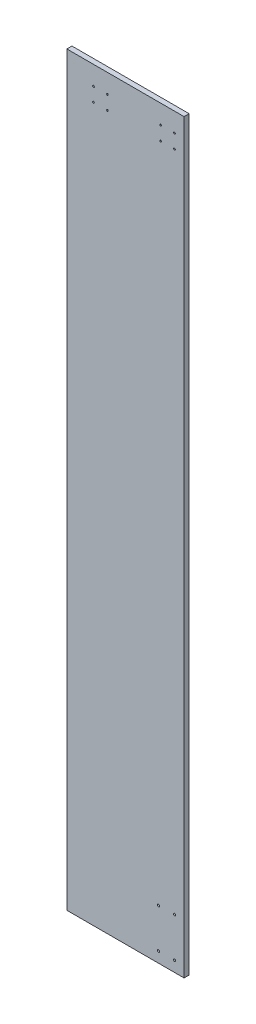
SolidWorks part; units mm, degrees
ref_plane "Front Plane" through (0, 0, 0) normal (0, 0, 1) x (1, 0, 0)
ref_plane "Top Plane" through (0, 0, 0) normal (0, 1, 0) x (1, 0, 0)
ref_plane "Right Plane" through (0, 0, 0) normal (1, 0, 0) x (0, 0, -1)
sketch "Sketch1" plane through (0, 0, 0) normal (0, 0, 1) x (-1, 0, 0)
  line L1 (0, 0) -> (-220, 0)
  line L2 (0, 0) -> (0, -1400)
  line L3 (0, -1400) -> (-220, -1400)
  line L4 (-220, 0) -> (-220, -1400)
  circle A12 centre (-202, -20) radius 2.065
  circle A13 centre (-172, -20) radius 2.065
  circle A14 centre (-202, -94) radius 2.065
  circle A15 centre (-172, -94) radius 2.065
  circle A16 centre (-202, -1338.2) radius 1.621
  circle A17 centre (-176, -1338.2) radius 1.621
  circle A18 centre (-176, -1364.2) radius 1.621
  circle A19 centre (-202, -1364.2) radius 1.621
  circle A20 centre (-76, -1338.2) radius 1.621
  circle A21 centre (-50, -1338.2) radius 1.621
  circle A22 centre (-50, -1364.2) radius 1.621
  circle A23 centre (-76, -1364.2) radius 1.621
  dimension "D27" = 4.13
  dimension "D1" = 26
  dimension "D2" = 26
  dimension "D3" = 26
  dimension "D4" = 26
  dimension "D5" = 100
  dimension "D6" = 100
  dimension "D7" = 26
  dimension "D8" = 26
  dimension "D9" = 26
  dimension "D10" = 26
  dimension "D11" = 30
  dimension "D12" = 74
  dimension "D13" = 30
  dimension "D14" = 74
  dimension "D15" = 1244.2
  dimension "D16" = 0
  dimension "D17" = 50
  dimension "D18" = 20
  dimension "D19" = 1244.2
  dimension "D21" = 126
  dimension "D22" = 126
  dimension "D23" = 126
  dimension "D24" = 1400
  dimension "D25" = 220
  dimension "D26" = 0
extrude "Boss-Extrude1" add sketch "Sketch1" along normal blind 9.525
